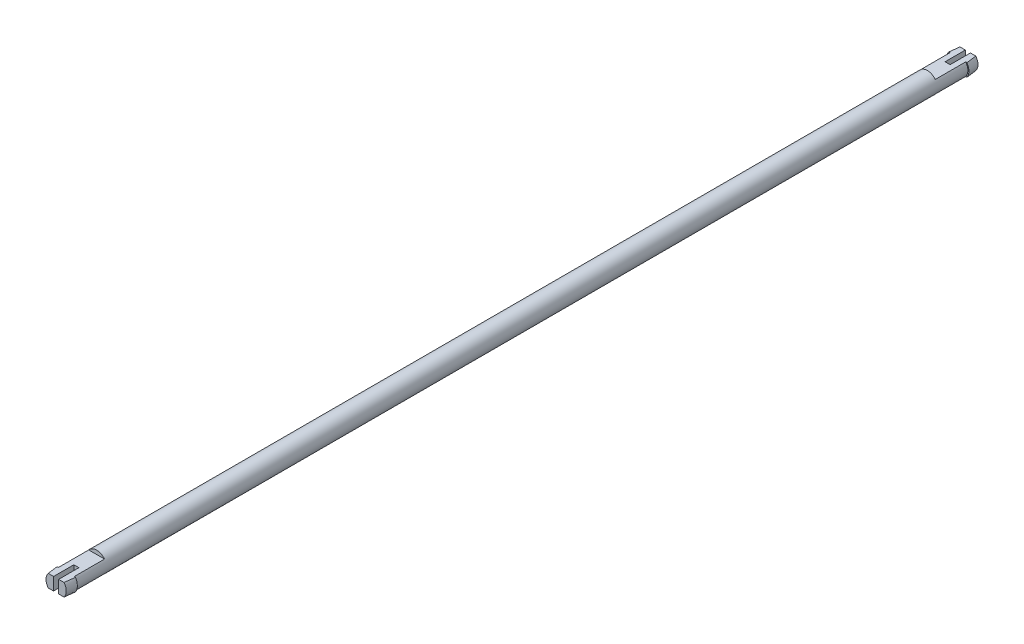
SolidWorks part; units mm, degrees
ref_plane "前视基准面" through (0, 0, 0) normal (0, 0, 1) x (1, 0, 0)
ref_plane "上视基准面" through (0, 0, 0) normal (0, 1, 0) x (1, 0, 0)
ref_plane "右视基准面" through (0, 0, 0) normal (1, 0, 0) x (0, 0, -1)
sketch "草图1" plane through (0, 0, 0) normal (0, 0, 1) x (1, 0, 0)
  circle A0 centre (0, 0) radius 2
extrude "凸台-拉伸1" add sketch "草图1" against normal blind 180
sketch "草图2" plane through (0, 0, 0) normal (0, 1, 0) x (1, 0, 0)
  line L0 (0, 0) -> (0, 2)
  line L1 (0, 2) -> (2.2, 2)
  line L2 (0, 0) -> (2, 0)
  line L3 (2, 0) -> (2.2, 2)
  dimension "D1" = 2.2
  dimension "D2" = 2
revolve "旋转1" add sketch "草图2" angle 360 about L0
sketch "草图3" plane through (0, 0, 0) normal (0, 0, 1) x (1, 0, 0)
  line L0 (-2.1, 1.25) -> (-2.1, 2.25)
  line L1 (-2.1, 1.25) -> (2.1, 1.25)
  line L2 (2.1, 1.25) -> (2.1, 2.25)
  line L3 (-2.1, -1.25) -> (2.1, -1.25)
  line L5 (-2.1, -2.25) -> (2.1, -2.25)
  line L6 (-2.1, -2.25) -> (-2.1, -1.25)
  line L7 (-2.1, 2.25) -> (2.1, 2.25)
  line L8 (2.1, -2.25) -> (2.1, -1.25)
  dimension "D1" = 1.25
  dimension "D2" = 1.25
  dimension "D3" = 1
  dimension "D4" = 1
extrude "切除-拉伸1" cut sketch "草图3" against normal blind 8
sketch "草图4" plane through (0, -1.25, 0) normal (0, -1, 0) x (1, 0, 0)
  line L0 (1.5612, 0) -> (-1.5612, 0) construction
  line L1 (-0.5, 0) -> (0.5, 0)
  line L2 (-0.5, 0) -> (-0.5, -4)
  line L3 (-0.5, -4) -> (0.5, -4)
  line L4 (0.5, 0) -> (0.5, -4)
extrude "切除-拉伸2" cut sketch "草图4" against normal up to next
sketch "草图5" plane through (0, 0, 0) normal (0, 1, 0) x (1, 0, 0)
  line L0 (0, 180) -> (0, 178)
  line L1 (2, 180) -> (-2, 180) construction
  line L2 (0, 178) -> (2.2, 178)
  line L3 (2.2, 178) -> (2, 180)
  line L4 (2, 180) -> (0, 180)
  line L5 (0, 58.1377) -> (0, 60.3241) construction
  dimension "D1" = 2.2
  dimension "D2" = 2
revolve "旋转2" add sketch "草图5" angle 360 about L5
sketch "草图6" plane through (0, 0, -180) normal (0, 0, -1) x (-1, 0, 0)
  line L1 (-2.1, 1.25) -> (2.1, 1.25)
  line L2 (-2.1, 1.25) -> (-2.1, 2.25)
  line L3 (-2.1, 2.25) -> (2.1, 2.25)
  line L4 (2.1, 1.25) -> (2.1, 2.25)
  line L5 (-2.1, -1.25) -> (2.1, -1.25)
  line L6 (-2.1, -1.25) -> (-2.1, -2.25)
  line L7 (-2.1, -2.25) -> (2.1, -2.25)
  line L8 (2.1, -1.25) -> (2.1, -2.25)
  dimension "D1" = 1.25
  dimension "D2" = 1.25
  dimension "D3" = 1
  dimension "D4" = 1
extrude "切除-拉伸3" cut sketch "草图6" against normal blind 8
sketch "草图7" plane through (0, 1.25, 0) normal (0, 1, 0) x (1, 0, 0)
  line L0 (0, 180) -> (0, 176) construction
  line L1 (-1.5612, 180) -> (1.5612, 180) construction
  line L2 (-0.5, 176) -> (0.5, 176)
  line L3 (0.5, 176) -> (0.5, 180)
  line L4 (0.5, 180) -> (-0.5, 180)
  line L5 (-0.5, 176) -> (-0.5, 180)
  dimension "D1" = 4
  dimension "D2" = 0.5
extrude "切除-拉伸4" cut sketch "草图7" against normal through all
